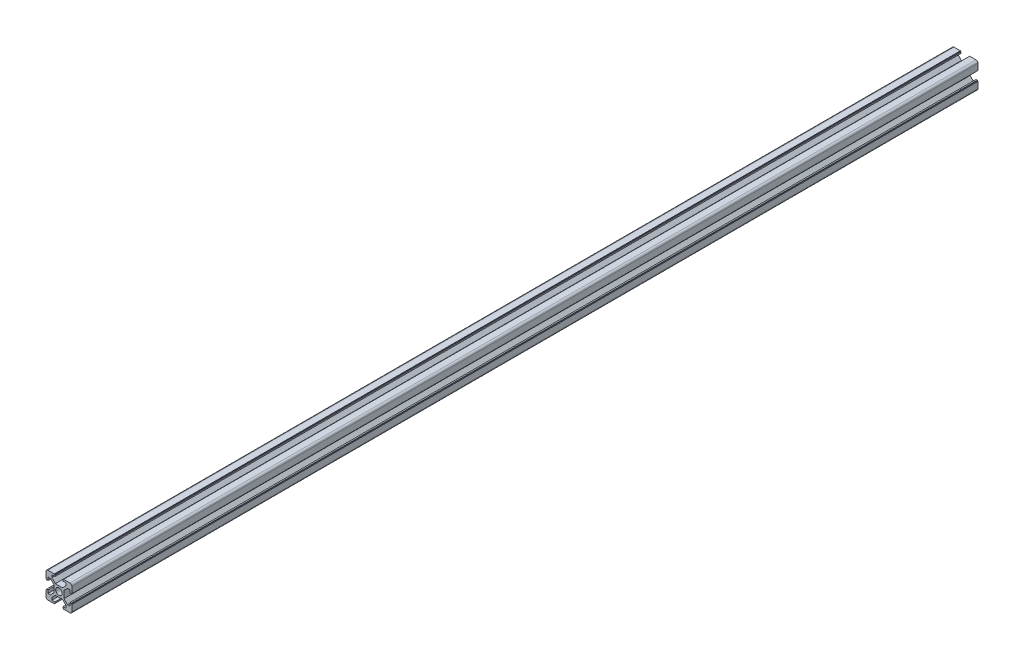
SolidWorks part; units mm, degrees
ref_plane "前视基准面" through (0, 0, 0) normal (0, 0, 1) x (1, 0, 0)
ref_plane "上视基准面" through (0, 0, 0) normal (0, 1, 0) x (1, 0, 0)
ref_plane "右视基准面" through (0, 0, 0) normal (1, 0, 0) x (0, 0, -1)
other "Configuration Table"
sketch "草图1" plane through (0, 0, 0) normal (1, 0, 0) x (0, 0, -1)
  line L0 (0, 0) -> (700, 0)
  dimension "D1" = 700
other "铝型材 20 X 20 X R1.5(1)"
ref_plane "基准面1" through (0, 0, 0) normal (0, 0, -1) x (0, 1, 0)
sketch "Sketch13" plane through (0, 0, 0) normal (0, 0, -1) x (0, 1, 0)
  line L0 (-3.6, 10) -> (-3.6, 9.5)
  line L1 (-3.6, 9.5) -> (-3.1, 9.5)
  line L2 (-3.1, 9.5) -> (-3.1, 8.5)
  line L3 (-3.1, 8.5) -> (-5.5, 8.5)
  line L4 (-8.5, -10) -> (-3.6, -10)
  line L5 (-10, -8.5) -> (-10, -3.6)
  line L6 (8.5, 10) -> (3.6, 10)
  line L7 (10, 8.5) -> (10, 3.6)
  line L8 (0, 14.8756) -> (0, 0) construction
  line L9 (0, 0) -> (14.1675, 0) construction
  line L10 (-5.5, 8.5) -> (-5.5, 6.65)
  line L11 (-5.5, 6.65) -> (-2.75, 3.9)
  line L12 (-2.75, 3.9) -> (2.75, 3.9)
  line L13 (5.5, 6.65) -> (2.75, 3.9)
  line L14 (5.5, 8.5) -> (5.5, 6.65)
  line L15 (3.1, 8.5) -> (5.5, 8.5)
  line L16 (3.1, 9.5) -> (3.1, 8.5)
  line L17 (3.6, 9.5) -> (3.1, 9.5)
  line L18 (3.6, 10) -> (3.6, 9.5)
  line L19 (-3.6, 10) -> (-8.5, 10)
  line L20 (10, 3.6) -> (9.5, 3.6)
  line L21 (9.5, 3.6) -> (9.5, 3.1)
  line L22 (9.5, 3.1) -> (8.5, 3.1)
  line L23 (8.5, 3.1) -> (8.5, 5.5)
  line L24 (8.5, 5.5) -> (6.65, 5.5)
  line L25 (6.65, 5.5) -> (3.9, 2.75)
  line L26 (3.9, 2.75) -> (3.9, -2.75)
  line L27 (6.65, -5.5) -> (3.9, -2.75)
  line L28 (8.5, -5.5) -> (6.65, -5.5)
  line L29 (8.5, -3.1) -> (8.5, -5.5)
  line L30 (9.5, -3.1) -> (8.5, -3.1)
  line L31 (9.5, -3.6) -> (9.5, -3.1)
  line L32 (10, -3.6) -> (9.5, -3.6)
  line L33 (3.6, -10) -> (3.6, -9.5)
  line L34 (3.6, -9.5) -> (3.1, -9.5)
  line L35 (3.1, -9.5) -> (3.1, -8.5)
  line L36 (3.1, -8.5) -> (5.5, -8.5)
  line L37 (5.5, -8.5) -> (5.5, -6.65)
  line L38 (5.5, -6.65) -> (2.75, -3.9)
  line L39 (2.75, -3.9) -> (-2.75, -3.9)
  line L40 (-5.5, -6.65) -> (-2.75, -3.9)
  line L41 (-5.5, -8.5) -> (-5.5, -6.65)
  line L42 (-3.1, -8.5) -> (-5.5, -8.5)
  line L43 (-3.1, -9.5) -> (-3.1, -8.5)
  line L44 (-3.6, -9.5) -> (-3.1, -9.5)
  line L45 (-3.6, -10) -> (-3.6, -9.5)
  line L46 (-10, -3.6) -> (-9.5, -3.6)
  line L47 (-9.5, -3.6) -> (-9.5, -3.1)
  line L48 (-9.5, -3.1) -> (-8.5, -3.1)
  line L49 (-8.5, -3.1) -> (-8.5, -5.5)
  line L50 (-8.5, -5.5) -> (-6.65, -5.5)
  line L51 (-6.65, -5.5) -> (-3.9, -2.75)
  line L52 (-3.9, -2.75) -> (-3.9, 2.75)
  line L53 (-6.65, 5.5) -> (-3.9, 2.75)
  line L54 (-8.5, 5.5) -> (-6.65, 5.5)
  line L55 (-8.5, 3.1) -> (-8.5, 5.5)
  line L56 (-9.5, 3.1) -> (-8.5, 3.1)
  line L57 (-9.5, 3.6) -> (-9.5, 3.1)
  line L58 (-10, 3.6) -> (-9.5, 3.6)
  line L59 (3.6, -10) -> (8.5, -10)
  line L60 (-10, 3.6) -> (-10, 8.5)
  line L61 (10, -3.6) -> (10, -8.5)
  circle A0 centre (0, 0) radius 2.5
  arc A1 (-10, 8.5) -> (-8.5, 10) centre (-8.5, 8.5) cw
  arc A2 (10, 8.5) -> (8.5, 10) centre (8.5, 8.5) ccw
  arc A3 (-8.5, -10) -> (-10, -8.5) centre (-8.5, -8.5) cw
  arc A4 (8.5, -10) -> (10, -8.5) centre (8.5, -8.5) ccw
  point P0 (-10, 0)
  point P1 (10, 0)
  point P2 (0, 10)
  point P3 (0, -10)
  point P4 (0, 0)
  point P5 (-10, -10)
  point P6 (10, -10)
  point P7 (10, 10)
  point P8 (-10, 10)
  point P13 (0, 0)
  point P36 (-10, 10)
  point P39 (10, 10)
  dimension "D1" = 11
  dimension "D2" = 20
  dimension "D3" = 6.2
  dimension "D4" = 7.2
  dimension "D5" = 6.1
  dimension "D6" = 5
  dimension "D7" = 1.5
  dimension "D8" = 45
  dimension "D9" = 0.5
  dimension "D10" = 1
  dimension "D11" = 5.5
